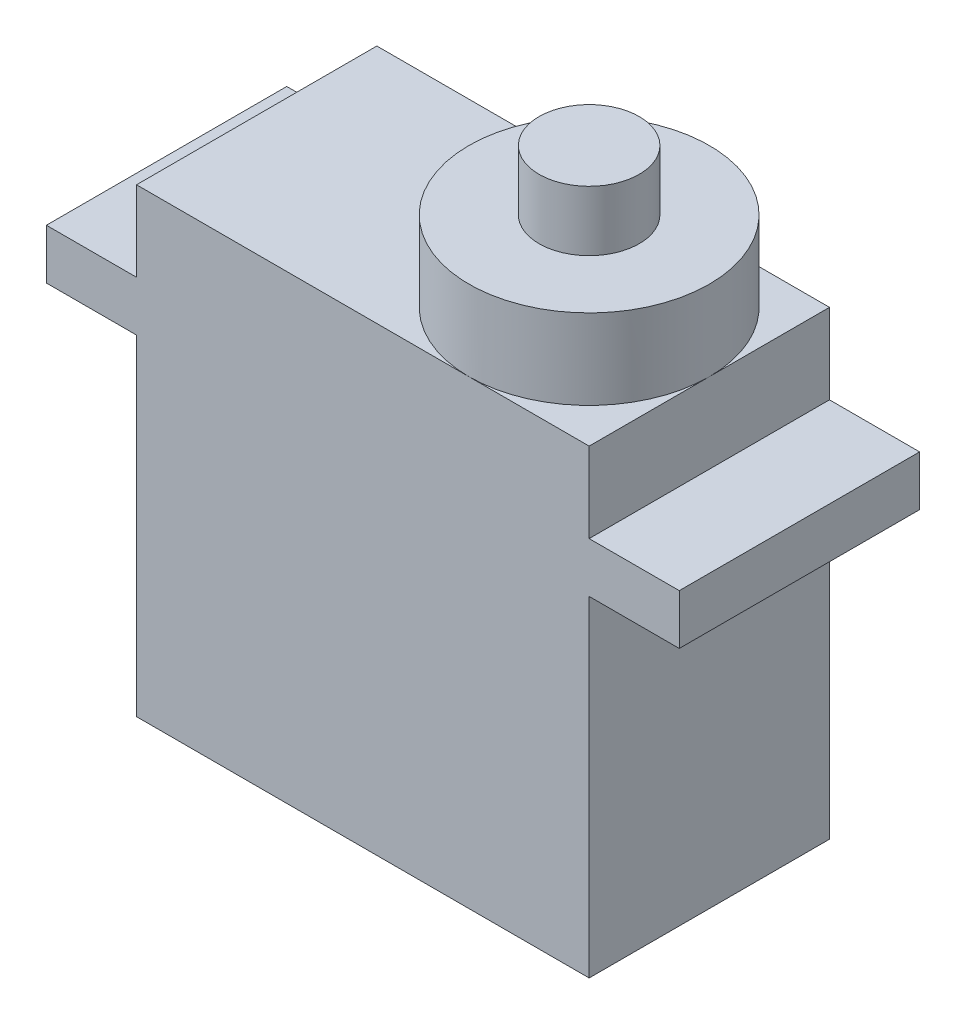
SolidWorks part; units mm, degrees
ref_plane "Front Plane" through (0, 0, 0) normal (0, 0, 1) x (1, 0, 0)
ref_plane "Top Plane" through (0, 0, 0) normal (0, 1, 0) x (1, 0, 0)
ref_plane "Right Plane" through (0, 0, 0) normal (1, 0, 0) x (0, 0, -1)
sketch "Sketch1" plane through (0, 0, 0) normal (0, 0, 1) x (1, 0, 0)
  line L1 (0, 0) -> (0, 16.5)
  line L2 (0, 16.5) -> (4.5, 16.5)
  line L3 (4.5, 16.5) -> (4.5, 19)
  line L4 (4.5, 19) -> (0, 19)
  line L5 (0, 19) -> (0, 23)
  line L6 (0, 23) -> (-22.6, 23)
  line L7 (-22.6, 23) -> (-22.6, 19)
  line L8 (-22.6, 19) -> (-27.1, 19)
  line L9 (-27.1, 19) -> (-27.1, 16.5)
  line L10 (-27.1, 16.5) -> (-22.6, 16.5)
  line L11 (-22.6, 16.5) -> (-22.6, 0)
  line L12 (-22.6, 0) -> (0, 0)
  point P1 (0, 0)
  point P13 (-12.5774, 11.7051)
  point P15 (0, 0)
  point P16 (0, 0)
  point P17 (0, 0)
  point P18 (-5.2444, 23)
  point P19 (0, 0)
  point P20 (0, 0)
  dimension "D1" = 22.6
  dimension "D2" = 16.5
  dimension "D3" = 19
  dimension "D4" = 23
  dimension "D5" = 4.5
extrude "Boss-Extrude1" add sketch "Sketch1" along normal blind 12
sketch "Sketch2" plane through (0, 23, 0) normal (0, 1, 0) x (1, 0, 0)
  line L0 (0, -12) -> (-22.6, -12) construction
  line L1 (0, 0) -> (-22.6, 0) construction
  line L2 (0, -12) -> (-22.6, -12)
  line L3 (0, 0) -> (-22.6, 0)
  line L4 (-6, -12) -> (-6, 0) construction
  line L6 (0, -12) -> (0, 0) construction
  circle A0 centre (-6, -6) radius 6
  point P8 (0, 0)
  point P9 (-5.6295, -6)
  point P10 (-5.7124, 0)
  dimension "D1" = 12
extrude "Boss-Extrude2" add sketch "Sketch2" along normal blind 4 contours A0 L4 | L4 A0
sketch "Sketch3" plane through (0, 27, 0) normal (0, 1, 0) x (1, 0, 0)
  circle A0 centre (-6, -6) radius 2.5
  circle A1 centre (-6, -6) radius 6 construction
  dimension "D1" = 5
extrude "Boss-Extrude3" add sketch "Sketch3" along normal blind 3
